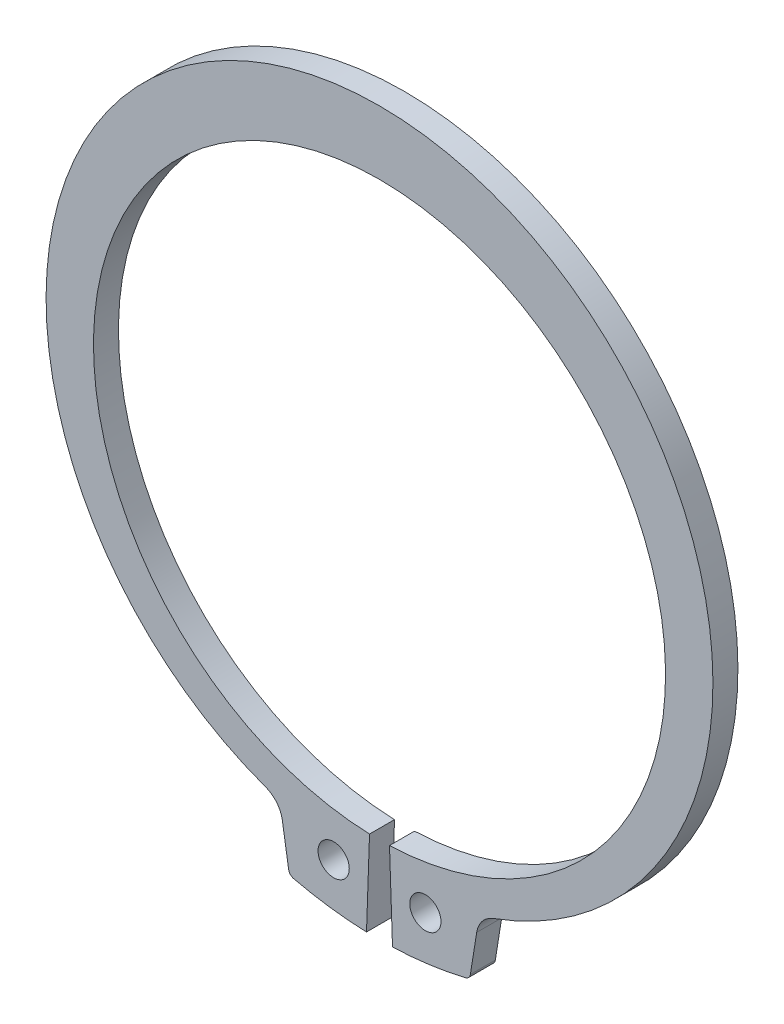
SolidWorks part; units mm, degrees
ref_plane "Front" through (0, 0, 0) normal (0, 0, 1) x (1, 0, 0)
ref_plane "Top" through (0, 0, 0) normal (0, 1, 0) x (1, 0, 0)
ref_plane "Right" through (0, 0, 0) normal (1, 0, 0) x (0, 0, -1)
sketch "Sketch1" plane through (0, 0, 0) normal (0, 0, 1) x (1, 0, 0)
  line L0 (0, 0) -> (-19.832, -11.45) construction
  line L1 (0, 29.8) -> (0, -29.8) construction
  line L2 (-7.2184, -28.9313) -> (-7.9795, -24.1667) construction
  line L4 (-7.9795, -24.1667) -> (-8.779, -26.5881) construction
  line L5 (-7.9795, -24.1667) -> (0, 0) construction
  line L6 (0, 22.9) -> (0, 28) construction
  line L7 (0, 28) -> (0, 25.45) construction
  line L8 (0, -22.9) -> (0, -29.8) construction
  line L9 (-4.1523, -29.5276) -> (0, 0) construction
  line L10 (0, 0) -> (-1.0406, -29.8) construction
  line L11 (-7.2184, -28.9313) -> (0, 0) construction
  line L12 (-7.7876, -25.3682) -> (-9.132, -23.7766) construction
  line L13 (-8.4598, -24.5724) -> (-7.9795, -24.1667) construction
  line L14 (-3.1889, -22.6769) -> (-4.1523, -29.5276) construction
  line L15 (-3.6706, -26.1023) -> (-2.4328, -26.2763) construction
  arc A0 (0, 28) -> (-7.9795, -24.1667) centre (0, 1.3064) ccw construction
  circle A2 centre (0, 0) radius 28 construction
  arc A3 (-7.2184, -28.9313) -> (-1.0406, -29.8) centre (0, 0) ccw construction
  circle A4 centre (0, 0) radius 22.9 construction
  circle A6 centre (-3.6706, -26.1023) radius 1.25 construction
  arc A7 (-9.132, -23.7766) -> (-7.7876, -25.3682) centre (-9.8489, -25.7458) cw construction
  circle A9 centre (0, 0) radius 25 construction
  circle A10 centre (0, 0) radius 23.5 construction
  point P5 (-19.832, -11.45)
  point P24 (-6.7783, -27.1672)
  point P35 (0, 28)
  point P36 (0, 22.9)
  point P37 (0, -22.9)
  point P38 (0, -29.8)
  dimension "Hole Diameter" = 2.5
  dimension "D10" = 2.0956
  dimension "For OD" = 50
  dimension "ID" = 45.8
  dimension "Max Sec." = 5.1
  dimension "Lug Height" = 6.9
  dimension "D6" = 2
  dimension "D5" = 4.8249
  dimension "D8" = 2.0833
  dimension "D3" = 120
  dimension "D2" = 6.25
  dimension "D4" = 2.0833
sketch "Sketch2" plane through (0, 0, 0) normal (-1, 0, 0) x (0, 1, 0)
  line L0 (-28, 1) -> (-28, -1) construction
  line L1 (28, -1.075) -> (28, 1.075) construction
  line L2 (0, 1) -> (0, -1) construction
  line L4 (-28, 0) -> (28, 0) construction
  point P3 (-28, 0)
  point P6 (0, 0)
  point P14 (28, 0)
  dimension "Thickness" = 2
  dimension "For Groove Width" = 2.15
sketch "Sketch4" plane through (0, 0, 0) normal (0, 0, 1) x (1, 0, 0)
  line L0 (-7.2184, -28.9313) -> (-7.9795, -24.1667) construction
  line L1 (-7.2184, -28.9313) -> (-7.9795, -24.1667)
  line L2 (0, 28) -> (0, 22.9)
  line L3 (-1.0406, -29.8) -> (-0.7992, -22.886)
  line L4 (0, 0) -> (-1.0406, -29.8) construction
  arc A0 (0, 28) -> (-7.9795, -24.1667) centre (0, 1.3064) ccw construction
  arc A1 (-7.2184, -28.9313) -> (-1.0406, -29.8) centre (0, 0) ccw construction
  circle A2 centre (-3.6706, -26.1023) radius 1.25 construction
  arc A4 (0, 28) -> (-7.9795, -24.1667) centre (0, 1.3064) ccw
  arc A5 (-7.2184, -28.9313) -> (-1.0406, -29.8) centre (0, 0) ccw
  circle A6 centre (-3.6706, -26.1023) radius 1.25
  circle A7 centre (0, 0) radius 22.9 construction
  arc A8 (0, 22.9) -> (-0.7992, -22.886) centre (0, 0) ccw
extrude "Boss-Extrude1" add sketch "Sketch4" along normal mid plane 2
fillet "Fillet1" radius 2.0956 1 edges at (-7.9795, -24.1667, 0)
fillet "Fillet2" radius 0.5239 1 edges at (-7.2184, -28.9313, 0)
mirror "Mirror1" about plane through (0, 28, 1) normal (-1, 0, 0) of bodies 109
sketch "Sketch3" plane through (0, 0, 1) normal (0, 0, 1) x (1, 0, 0)
  line L0 (8.2531, -21.3611) -> (9.1325, -23.7764) construction
  line L1 (9.1325, -23.7764) -> (11.5479, -22.897) construction
  line L2 (0, 28) -> (0, 22.9) construction
  circle A0 centre (0, 0) radius 22.9 construction
  arc A1 (9.1325, -23.7764) -> (-9.1325, -23.7764) centre (0, 1.3064) ccw construction
equation "\"D1@Fillet1\" = \"D10@Sketch1\""
equation "\"D1@Fillet2\" = \"D10@Sketch1\" / 4"
equation "\"Thickness@Boss-Extrude1\"  = \"Ring Thickness@Sketch5\""
equation "\"D2@Sketch1\"=\"Hole Diameter@Sketch1\"*2.5"
equation "\"D4@Sketch1\"=\"D2@Sketch1\"/3"
equation "\"D8@Sketch1\"=\"D4@Sketch1\""
